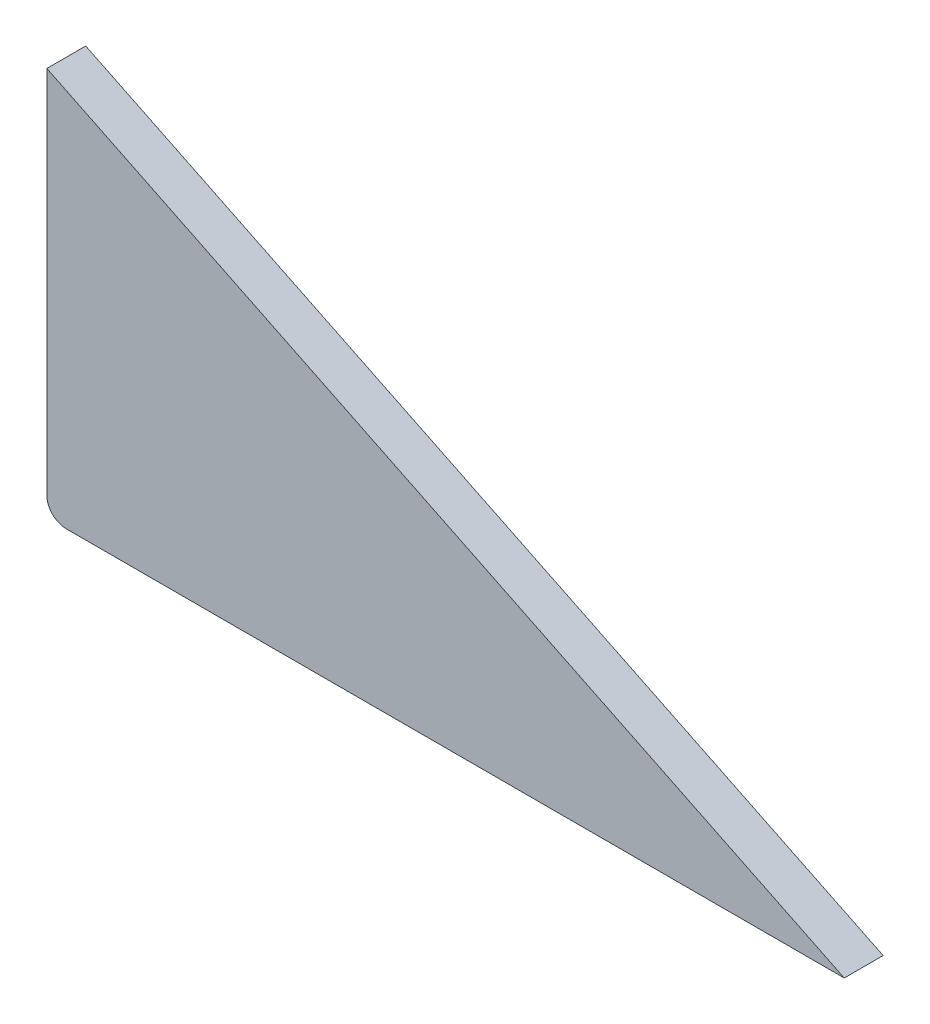
SolidWorks part; units mm, degrees
ref_plane "Front Plane" through (0, 0, 0) normal (0, 0, 1) x (1, 0, 0)
ref_plane "Top Plane" through (0, 0, 0) normal (0, 1, 0) x (1, 0, 0)
ref_plane "Right Plane" through (0, 0, 0) normal (1, 0, 0) x (0, 0, -1)
sketch "Sketch2" plane through (0, 0, 0) normal (0, 0, 1) x (1, 0, 0)
  line L0 (0, 0) -> (130.175, 0)
  line L1 (130.175, 0) -> (0, 63.5)
  line L2 (0, 63.5) -> (0, 0)
  dimension "D1" = 63.5
  dimension "D2" = 130.175
extrude "Boss-Extrude1" add sketch "Sketch2" along normal blind 6.35
fillet "Fillet1" radius 3.175 1 edges at (0, 0, 3.175)
